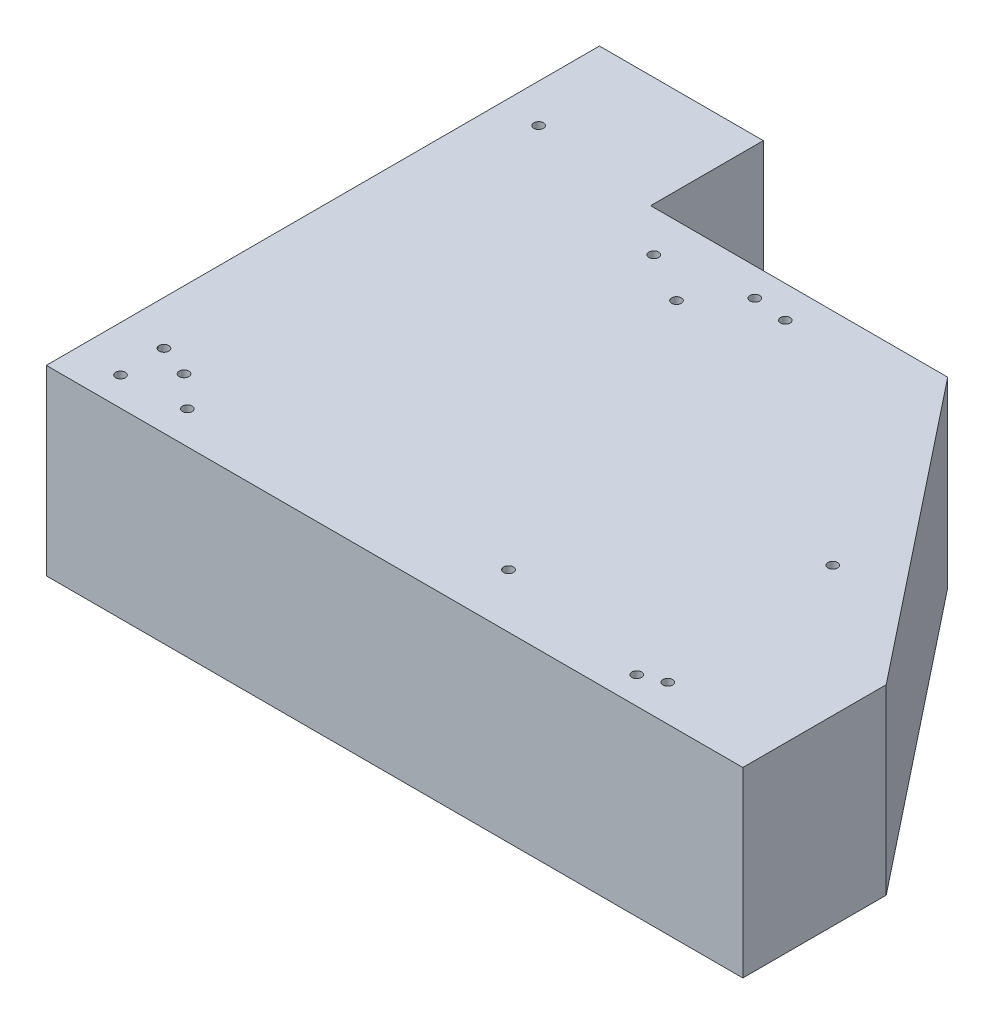
SolidWorks part; units mm, degrees
material "6061-T6 (SS)"
ref_plane "Front Plane" through (0, 0, 0) normal (0, 0, 1) x (1, 0, 0)
ref_plane "Top Plane" through (0, 0, 0) normal (0, 1, 0) x (1, 0, 0)
ref_plane "Right Plane" through (0, 0, 0) normal (1, 0, 0) x (0, 0, -1)
sketch "Sketch1" plane through (0, 0, 0) normal (0, 1, 0) x (1, 0, 0)
  line L5 (-187.5, -135.6424) -> (244.3, -135.6424)
  line L6 (244.3, -135.6424) -> (244.3, -46.7424)
  line L9 (-187.5, -135.6424) -> (-187.5, 207.2576)
  line L11 (-187.5, 207.2576) -> (-85.9, 207.2576)
  line L12 (-85.9, 207.2576) -> (-85.9, 137.4076)
  line L13 (-85.9, 137.4076) -> (98.25, 137.4076)
  line L14 (98.25, 137.4076) -> (244.3, -46.7424)
  point P0 (0, 0)
extrude "ALUMINUM BLOCK" add sketch "Sketch1" along normal blind 113.03
sketch "A-ARM SKETCHES" plane through (0, 113.03, 0) normal (0, 1, 0) x (1, 0, 0)
  circle A0 centre (-163.6091, 145.6958) radius 3
  circle A1 centre (-3.8989, 120.0153) radius 3
  circle A2 centre (-140.2518, -97.5172) radius 3
  circle A3 centre (161.6067, -118.7297) radius 3
  circle A4 centre (163.6037, 0.7881) radius 3
  circle A5 centre (65.4788, -102.1009) radius 3
  circle A6 centre (-58.545, 112.0368) radius 3
  circle A7 centre (175.3112, -113.1496) radius 3
  circle A8 centre (-160.1589, -90.0364) radius 3
  circle A9 centre (-159.3225, -117.8223) radius 3
  circle A10 centre (-120.4504, -115.2517) radius 3
  circle A11 centre (17.3942, 117.6269) radius 3
  circle A12 centre (-26.9081, 94.4471) radius 3
  line B0 (175.3112, -113.1496) -> (-58.545, 112.0368) construction
  line B1 (175.3112, -113.1496) -> (-140.2518, -97.5172) construction
  line B2 (-160.1589, -90.0364) -> (65.4788, -102.1009) construction
  line B3 (-160.1589, -90.0364) -> (17.3942, 117.6269) construction
  line B4 (17.3942, 117.6269) -> (-26.9081, 94.4471) construction
  line B5 (163.6037, 0.7881) -> (-159.3225, -117.8223) construction
  line B6 (163.6037, 0.7881) -> (-163.6091, 145.6958) construction
  line B7 (161.6067, -118.7297) -> (-120.4504, -115.2517) construction
  line B8 (161.6067, -118.7297) -> (-3.8989, 120.0153) construction
sketch_block_instance "REAR LOWER-1"
sketch_block "REAR LOWER" parameters "D1"=41.082, "D2"=324.65, "D3"=315.95
sketch_block_instance "REAR UPPER-1"
sketch_block "REAR UPPER" parameters "D1"=52.53, "D2"=225.96, "D3"=273.22, "D4"=50
sketch_block_instance "FRONT LOWER-1"
sketch_block "FRONT LOWER" parameters "D1"=44.055, "D2"=357.8638, "D3"=344.02
sketch_block_instance "FRONT UPPER-1"
sketch_block "FRONT UPPER" parameters "D1"=54.563, "D2"=282.0785, "D3"=290.5017
extrude "A-ARM HOLES" cut sketch "A-ARM SKETCHES" against normal blind 20 contours A0 | A1 | A7 | A8 | A9 | A10 | A6 | A5 | A4 | A3 | A2 | A11 | A12
